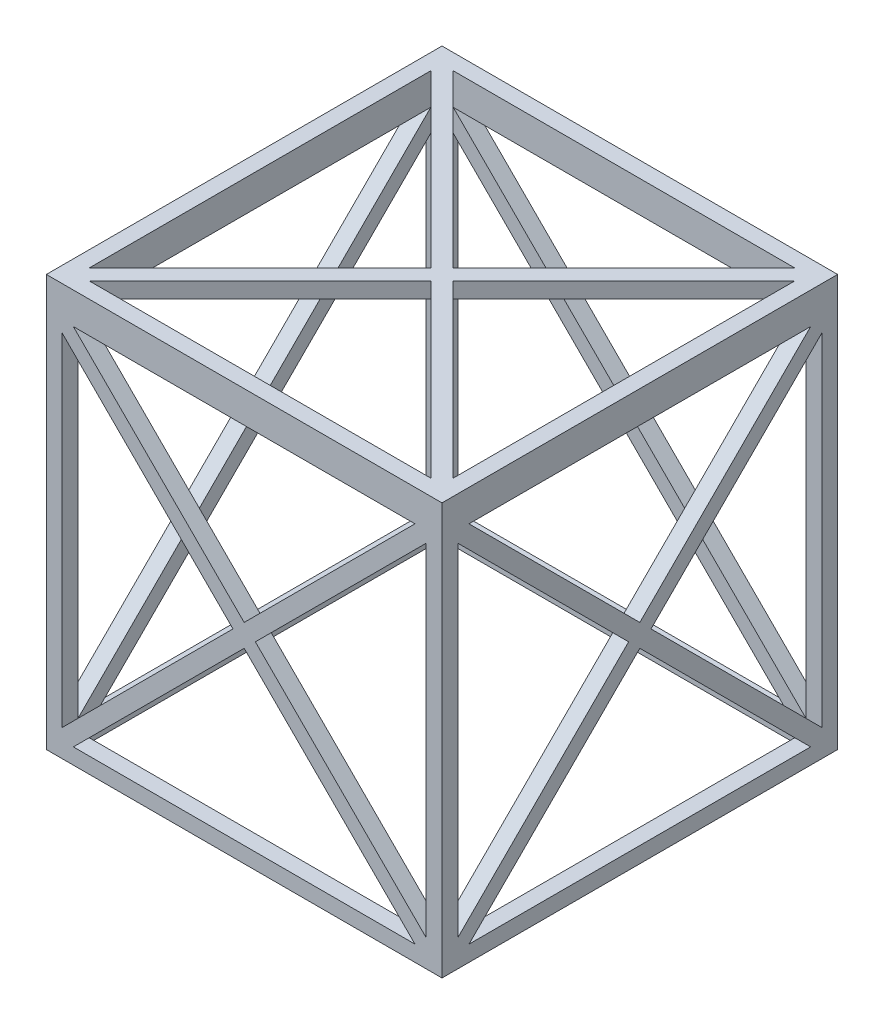
SolidWorks part; units mm, degrees
ref_plane "Front Plane" through (0, 0, 0) normal (0, 0, 1) x (1, 0, 0)
ref_plane "Top Plane" through (0, 0, 0) normal (0, 1, 0) x (1, 0, 0)
ref_plane "Right Plane" through (0, 0, 0) normal (1, 0, 0) x (0, 0, -1)
ref_plane "Front Face" through (0, 0, 50) normal (0, 0, 1) x (1, 0, 0)
sketch "Sketch1" plane through (0, 0, 50) normal (0, 0, 1) x (1, 0, 0)
  line L5 (-43.1716, 46) -> (43.1716, 46)
  line L6 (-50, -50) -> (50, -50)
  line L10 (-50, -50) -> (-50, 50)
  line L11 (-50, 50) -> (50, 50)
  line L12 (50, -50) -> (50, 50)
  line L13 (-50, -50) -> (50, 50) construction
  line L14 (-50, 50) -> (50, -50) construction
  line L15 (46, -43.1716) -> (46, 43.1716)
  line L16 (-43.1716, -46) -> (43.1716, -46)
  line L17 (-46, -43.1716) -> (-46, 43.1716)
  line L18 (-46, 43.1716) -> (-2.8284, 0)
  line L19 (-43.1716, -46) -> (0, -2.8284)
  line L20 (-43.1716, 46) -> (0, 2.8284)
  line L21 (-46, -43.1716) -> (-2.8284, 0)
  line L22 (-51.4142, 48.5858) -> (48.5858, -51.4142) construction
  line L23 (-48.5858, 51.4142) -> (51.4142, -48.5858) construction
  line L24 (-46, 46) -> (46, 46) construction
  line L25 (-46, -46) -> (-46, 46) construction
  line L26 (46, -46) -> (46, 46) construction
  line L27 (-46, -46) -> (46, -46) construction
  line L28 (-51.4142, -48.5858) -> (48.5858, 51.4142) construction
  line L29 (2.8284, 0) -> (46, 43.1716)
  line L30 (-48.5858, -51.4142) -> (51.4142, 48.5858) construction
  line L31 (0, -2.8284) -> (43.1716, -46)
  line L32 (2.8284, 0) -> (46, -43.1716)
  line L33 (0, 2.8284) -> (43.1716, 46)
  point P0 (0, 0)
  dimension "D1" = 100
  dimension "D2" = 4
  dimension "D3" = 2
  dimension "D4" = 2
extrude "Boss-Extrude1" add sketch "Sketch1" against normal blind 4
mirror "Mirror2" about plane through (0, 0, 0) normal (0, 0, 1) of bodies 101
sketch "Sketch9" plane through (50, 0, 0) normal (1, 0, 0) x (0, 0, -1)
  line L5 (43.1716, 46) -> (-43.1716, 46)
  line L6 (50, -50) -> (-50, -50)
  line L10 (50, -50) -> (50, 50)
  line L11 (50, 50) -> (-50, 50)
  line L12 (-50, -50) -> (-50, 50)
  line L13 (50, -50) -> (-50, 50) construction
  line L14 (50, 50) -> (-50, -50) construction
  line L15 (-46, -43.1716) -> (-46, 43.1716)
  line L16 (43.1716, -46) -> (-43.1716, -46)
  line L17 (46, -43.1716) -> (46, 43.1716)
  line L18 (51.4142, 48.5858) -> (-48.5858, -51.4142) construction
  line L19 (46, -43.1716) -> (2.8284, 0)
  line L20 (46, 43.1716) -> (2.8284, 0)
  line L21 (43.1716, -46) -> (0, -2.8284)
  line L22 (48.5858, -51.4142) -> (-51.4142, 48.5858) construction
  line L23 (51.4142, -48.5858) -> (-48.5858, 51.4142) construction
  line L24 (-46, -46) -> (-46, 46) construction
  line L25 (46, 46) -> (-46, 46) construction
  line L26 (43.1716, 46) -> (0, 2.8284)
  line L27 (46, -46) -> (46, 46) construction
  line L28 (0, -2.8284) -> (-43.1716, -46)
  line L29 (-2.8284, 0) -> (-46, 43.1716)
  line L30 (0, 2.8284) -> (-43.1716, 46)
  line L31 (-2.8284, 0) -> (-46, -43.1716)
  line L32 (46, -46) -> (-46, -46) construction
  point P0 (0, 0)
  dimension "D3" = 2
  dimension "D4" = 2
  dimension "D1" = 4
  dimension "D2" = 2
extrude "Boss-Extrude2" add sketch "Sketch9" against normal blind 4
mirror "Mirror3" about plane through (0, 0, 0) normal (1, 0, 0) of "Boss-Extrude2"
sketch "Sketch10" plane through (0, 50, 0) normal (0, 1, 0) x (1, 0, 0)
  line L0 (-46, -43.1716) -> (-46, 43.1716)
  line L1 (-50, -50) -> (50, -50)
  line L2 (-50, -50) -> (-50, 50)
  line L3 (-50, 50) -> (50, 50)
  line L4 (50, -50) -> (50, 50)
  line L5 (-50, -50) -> (50, 50) construction
  line L6 (-50, 50) -> (50, -50) construction
  line L7 (-43.1716, 46) -> (43.1716, 46)
  line L8 (46, -43.1716) -> (46, 43.1716)
  line L9 (-43.1716, -46) -> (43.1716, -46)
  line L10 (-46, 43.1716) -> (-2.8284, 0)
  line L11 (-43.1716, -46) -> (0, -2.8284)
  line L12 (-43.1716, 46) -> (0, 2.8284)
  line L13 (-46, -43.1716) -> (-2.8284, 0)
  line L14 (-51.4142, 48.5858) -> (48.5858, -51.4142) construction
  line L15 (-48.5858, 51.4142) -> (51.4142, -48.5858) construction
  line L16 (-46, -46) -> (-46, 46) construction
  line L17 (-46, 46) -> (46, 46) construction
  line L18 (46, -46) -> (46, 46) construction
  line L19 (2.8284, 0) -> (46, 43.1716)
  line L20 (-48.5858, -51.4142) -> (51.4142, 48.5858) construction
  line L21 (-46, -46) -> (46, -46) construction
  line L22 (-51.4142, -48.5858) -> (48.5858, 51.4142) construction
  line L23 (0, -2.8284) -> (43.1716, -46)
  line L24 (2.8284, 0) -> (46, -43.1716)
  line L25 (0, 2.8284) -> (43.1716, 46)
  point P0 (0, 0)
  dimension "D3" = 2
  dimension "D1" = 4
  dimension "D2" = 2
extrude "Boss-Extrude3" add sketch "Sketch10" along normal blind 4
equation "\"Thick\"=4"
equation "\"D2@Sketch1\"=\"Thick\""
equation "\"D4@Sketch1\"=\"hThick\""
equation "\"hThick\"= \"Thick\" / 2"
equation "\"D3@Sketch1\"=\"hThick\""
equation "\"D3@Sketch9\"=\"hThick\""
equation "\"D2@Sketch9\"=\"hThick\""
equation "\"D4@Sketch9\"=\"hThick\""
equation "\"D1@Boss-Extrude1\"=\"Thick\""
equation "\"D1@Boss-Extrude2\"=\"Thick\""
equation "\"D1@Sketch9\"=\"Thick\""
equation "\"D1@Sketch10\"=\"Thick\""
equation "\"D3@Sketch10\"=\"hThick\""
equation "\"D2@Sketch10\"=\"hThick\""
equation "\"D1@Boss-Extrude3\"=\"Thick\""
